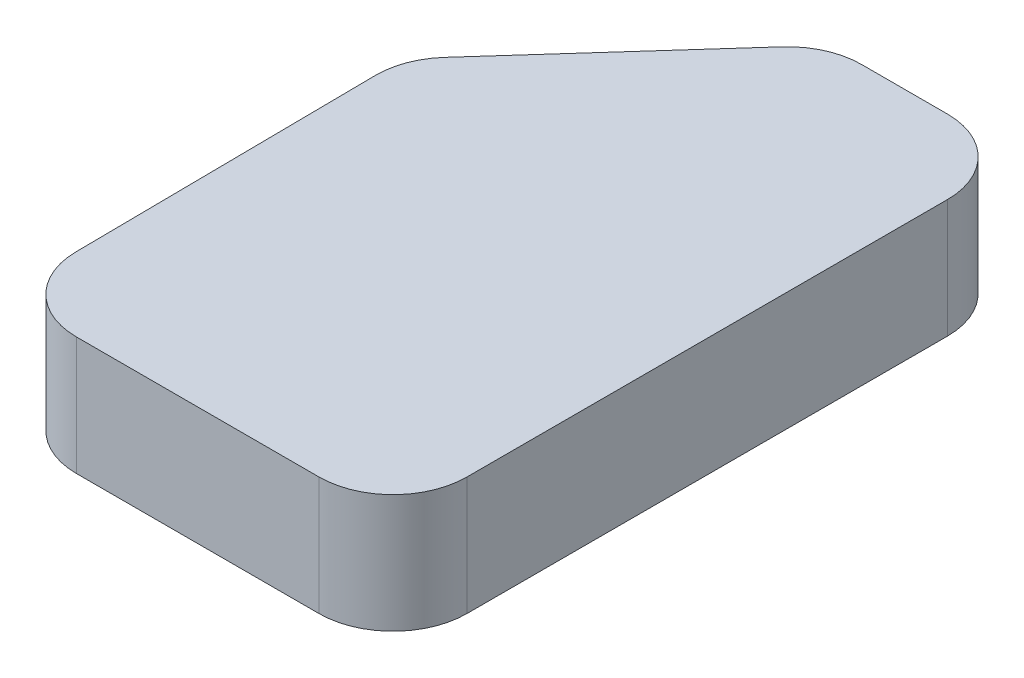
SolidWorks part; units mm, degrees
ref_plane "Plan de face" through (0, 0, 0) normal (0, 0, 1) x (1, 0, 0)
ref_plane "Plan de dessus" through (0, 0, 0) normal (0, 1, 0) x (1, 0, 0)
ref_plane "Plan de droite" through (0, 0, 0) normal (1, 0, 0) x (0, 0, -1)
sketch "Esquisse1" plane through (0, 0, 0) normal (0, 0, 1) x (1, 0, 0)
  line L1 (0, 0) -> (80, 0)
  line L2 (0, 0) -> (0, 16)
  line L3 (0, 16) -> (80, 16)
  line L4 (80, 0) -> (80, 16)
  dimension "D1" = 16
  dimension "D2" = 80
extrude "Boss.-Extru.1" add sketch "Esquisse1" along normal blind 85
sketch "Esquisse4" plane through (0, 16, 0) normal (0, 1, 0) x (1, 0, 0)
  line L1 (0, -60.0674) -> (50.9188, -3.3214)
  line L2 (0, -60.0674) -> (0, 0)
  line L3 (58.3617, 0) -> (0, 0)
  line L4 (80, 0) -> (0, 0)
  line L5 (0, 0) -> (0, -85)
  line L6 (0, -85) -> (80, -85)
  line L7 (80, -85) -> (80, 0)
  line L8 (80, 0) -> (0, 0)
  line L9 (0, 0) -> (0, -85)
  line L10 (0, -85) -> (80, -85)
  line L11 (80, -85) -> (80, 0)
  arc A0 (50.9188, -3.3214) -> (58.3617, 0) centre (58.3617, -10) cw
  line M5 (80, 0) -> (0, 0)
  line M6 (0, 0) -> (0, -85)
  dimension "D1" = 0
extrude "Enlèv. mat.-Extru.1" cut sketch "Esquisse4" against normal through all contours L1 A0 M5 M6
fillet "Congé1" radius 10 1 edges at (0, 8, 60.0674)
sketch "Esquisse5" plane through (0, 0, 0) normal (0, -1, 0) x (-1, 0, 0)
  line L0 (-27.2998, -85) -> (-26.738, -30.2695)
  line L1 (0, -85) -> (-80, -85) construction
  line L2 (-2.5571, -57.2176) -> (-50.9188, -3.3214) construction
  line L3 (-27.2998, -85) -> (23.0231, -85)
  line L4 (23.0231, -85) -> (25.9619, -37.419)
  line L5 (25.9619, -37.419) -> (-26.738, -30.2695)
extrude "Enlèv. mat.-Extru.2" cut sketch "Esquisse5" against normal through all
fillet "Congé2" radius 10 4 edges at (80, 8, 0) (80, 8, 85) (27.2998, 8, 85) (26.738, 8, 30.2695)
